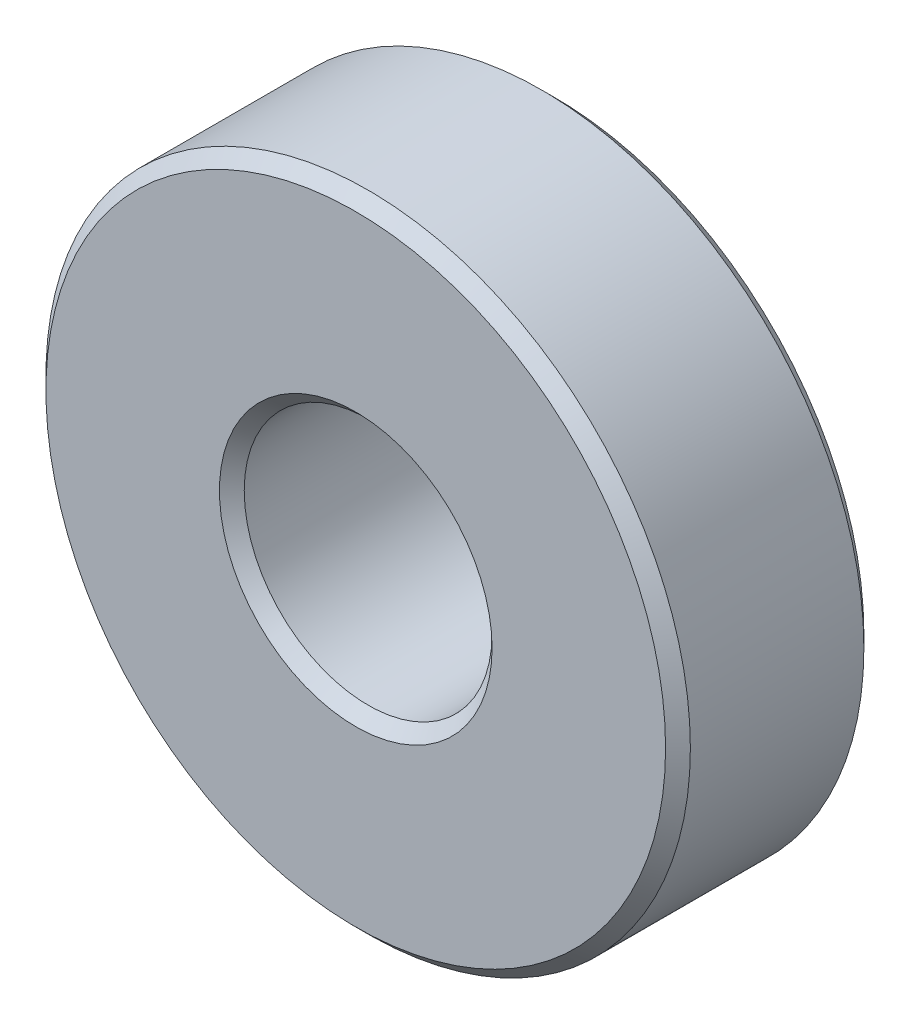
SolidWorks part; units mm, degrees
ref_plane "Front Plane" through (0, 0, 0) normal (0, 0, 1) x (1, 0, 0)
ref_plane "Top Plane" through (0, 0, 0) normal (0, 1, 0) x (1, 0, 0)
ref_plane "Right Plane" through (0, 0, 0) normal (1, 0, 0) x (0, 0, -1)
sketch "Sketch1" plane through (0, 0, 0) normal (0, 0, 1) x (1, 0, 0)
  circle A0 centre (0, 0) radius 13
  dimension "D1" = 26
extrude "Boss-Extrude1" add sketch "Sketch1" along normal blind 8
sketch "Sketch2" plane through (0, 0, 8) normal (0, 0, 1) x (1, 0, 0)
  circle A0 centre (0, 0) radius 5
  dimension "D1" = 10
extrude "Cut-Extrude1" cut sketch "Sketch2" against normal blind 8
chamfer "Chamfer1" distance 0.5 angle 45 4 edges at (5, 0, 0) (13, 0, 0) (5, 0, 8) (13, 0, 8)
